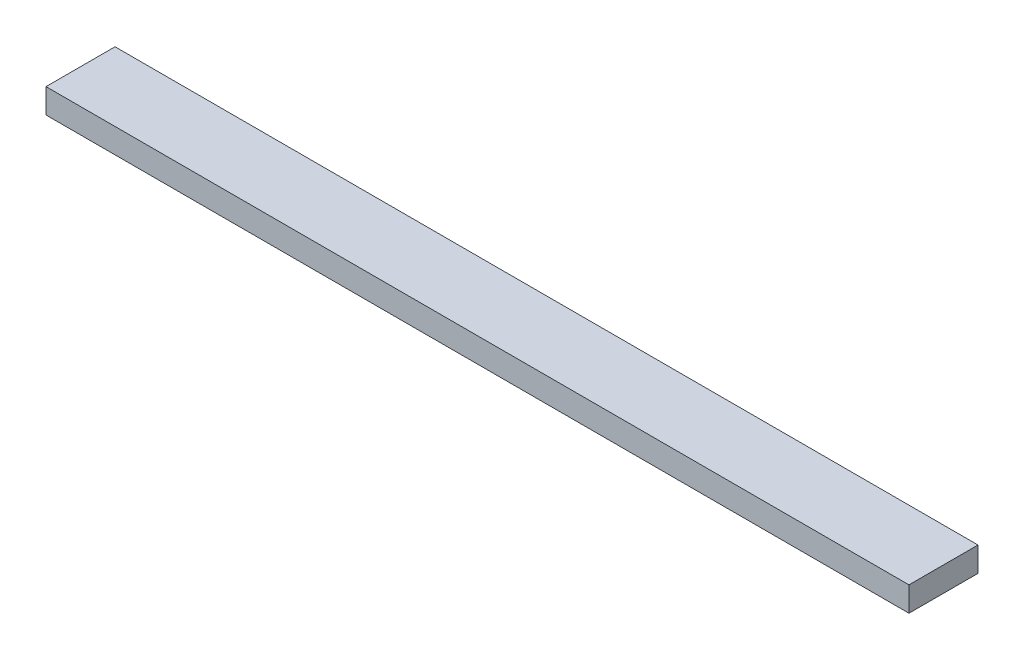
SolidWorks part; units mm, degrees
ref_plane "Front" through (0, 0, 0) normal (0, 0, 1) x (1, 0, 0)
ref_plane "Top" through (0, 0, 0) normal (0, 1, 0) x (1, 0, 0)
ref_plane "Right" through (0, 0, 0) normal (1, 0, 0) x (0, 0, -1)
sketch "Sketch1" plane through (0, 0, 0) normal (0, 1, 0) x (1, 0, 0)
  line L1 (-50, 4) -> (50, 4)
  line L2 (-50, 4) -> (-50, -4)
  line L3 (-50, -4) -> (50, -4)
  line L4 (50, 4) -> (50, -4)
  line L5 (-50, 4) -> (50, -4) construction
  line L6 (-50, -4) -> (50, 4) construction
  point P0 (0, 0)
  dimension "D1" = 8
  dimension "D2" = 100
extrude "Boss-Extrude1" add sketch "Sketch1" along normal blind 2.85
